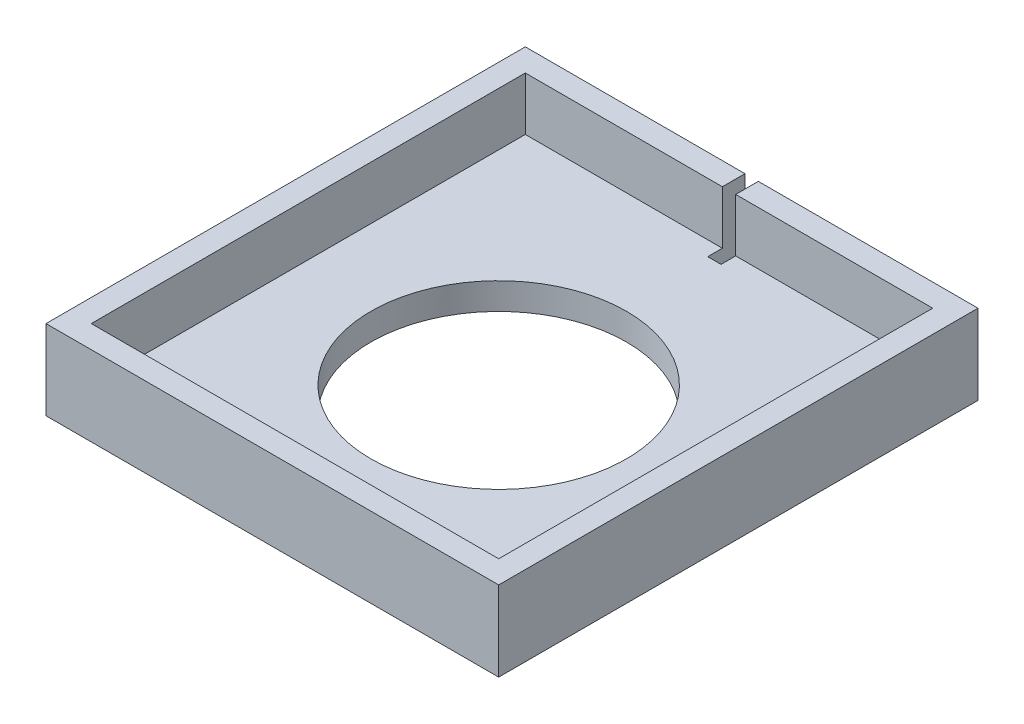
SolidWorks part; units mm, degrees
ref_plane "Front Plane" through (0, 0, 0) normal (0, 0, 1) x (1, 0, 0)
ref_plane "Top Plane" through (0, 0, 0) normal (0, 1, 0) x (1, 0, 0)
ref_plane "Right Plane" through (0, 0, 0) normal (1, 0, 0) x (0, 0, -1)
sketch "Sketch1" plane through (0, 0, 0) normal (0, 1, 0) x (1, 0, 0)
  line L1 (0, 0) -> (34, 0)
  line L2 (0, 0) -> (0, 36)
  line L3 (0, 36) -> (34, 36)
  line L4 (34, 0) -> (34, 36)
  line L5 (0, 0) -> (34, 36) construction
  line L6 (0, 36) -> (34, 0) construction
  point P4 (17, 18)
  dimension "D1" = 36
  dimension "D2" = 34
extrude "Boss-Extrude1" add sketch "Sketch1" along normal blind 6
sketch "Sketch2" plane through (0, 6, 0) normal (0, 1, 0) x (1, 0, 0)
  line L8 (1.7, 34.3) -> (1.7, 1.7)
  line L9 (1.7, 1.7) -> (32.3, 1.7)
  line L10 (32.3, 1.7) -> (32.3, 34.3)
  line L11 (32.3, 34.3) -> (1.7, 34.3)
  line L12 (1.7, 34.3) -> (1.7, 1.7)
  line L13 (1.7, 1.7) -> (32.3, 1.7)
  line L14 (32.3, 1.7) -> (32.3, 34.3)
  line L15 (32.3, 34.3) -> (1.7, 34.3)
  dimension "D1" = 1.7
extrude "Cut-Extrude1" cut sketch "Sketch2" against normal blind 4
sketch "Sketch3" plane through (0, 0, 0) normal (0, -1, 0) x (1, 0, 0)
  line L0 (17, 0) -> (17, -36) construction
  line L1 (0, 0) -> (34, 0) construction
  line L2 (34, -36) -> (0, -36) construction
  circle A0 centre (17, -17) radius 9.6
  dimension "D1" = 19.2
  dimension "D2" = 19
extrude "Cut-Extrude2" cut sketch "Sketch3" against normal through all
sketch "Sketch4" plane through (0, 0, 0) normal (0, -1, 0) x (1, 0, 0)
  line L0 (17, -36) -> (17, 0) construction
  line L1 (34, -36) -> (0, -36) construction
  line L2 (0, 0) -> (34, 0) construction
  line L4 (17.5, -36) -> (16.5, -36)
  line L5 (17.5, -36) -> (17.5, -33.2)
  line L6 (17.5, -33.2) -> (16.5, -33.2)
  line L7 (16.5, -36) -> (16.5, -33.2)
  line L8 (17.5, -36) -> (16.5, -33.2) construction
  line L9 (17.5, -33.2) -> (16.5, -36) construction
  point P10 (17, -34.6)
  dimension "D1" = 1
  dimension "D2" = 2.8
extrude "Cut-Extrude3" cut sketch "Sketch4" against normal through all
